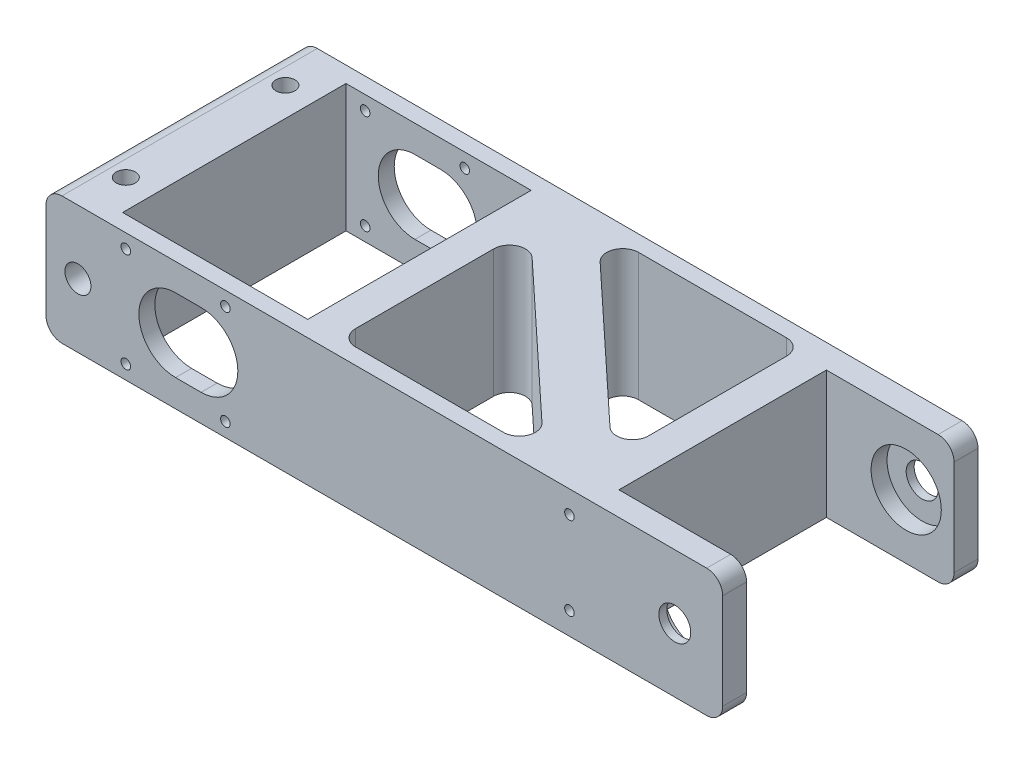
SolidWorks part; units mm, degrees
ref_plane "Front Plane" through (0, 0, 0) normal (0, 0, 1) x (1, 0, 0)
ref_plane "Top Plane" through (0, 0, 0) normal (0, 1, 0) x (1, 0, 0)
ref_plane "Right Plane" through (0, 0, 0) normal (1, 0, 0) x (0, 0, -1)
sketch "Sketch1" plane through (0, 0, 0) normal (0, 0, 1) x (1, 0, 0)
  line L0 (-106, -20) -> (-106, 20)
  line L1 (-106, 20) -> (106, 20)
  line L3 (-106, -20) -> (106, -20)
  line L4 (106, 20) -> (106, -20)
  line L5 (-106, 20) -> (106, -20) construction
  line L6 (-106, -20) -> (106, 20) construction
  line L7 (-81, 15.6) -> (-81, -15.6) construction
  line L8 (58, -13) -> (58, 13) construction
  line L9 (-81, 15.6) -> (-73, 15.6) construction
  line L10 (-81, 17.1) -> (-73, 17.1) construction
  line L11 (-81, 14.1) -> (-73, 14.1) construction
  line L12 (-49.8, 15.6) -> (-41.8, 15.6) construction
  line L13 (-49.8, 17.1) -> (-41.8, 17.1) construction
  line L14 (-49.8, 14.1) -> (-41.8, 14.1) construction
  line L15 (-81, -15.6) -> (-73, -15.6) construction
  line L16 (-81, -14.1) -> (-73, -14.1) construction
  line L17 (-81, -17.1) -> (-73, -17.1) construction
  line L18 (-49.8, -15.6) -> (-41.8, -15.6) construction
  line L19 (-49.8, -14.1) -> (-41.8, -14.1) construction
  line L20 (-49.8, -17.1) -> (-41.8, -17.1) construction
  line L21 (-65.4, 0) -> (-57.4, 0) construction
  line L22 (-65.4, 11.5) -> (-57.4, 11.5)
  line L23 (-65.4, -11.5) -> (-57.4, -11.5)
  circle A0 centre (-96, 0) radius 4.075
  circle A1 centre (-81, 15.6) radius 1.5
  circle A2 centre (-49.8, 15.6) radius 1.5
  circle A3 centre (-81, -15.6) radius 1.5
  circle A4 centre (-49.8, -15.6) radius 1.5
  circle A5 centre (-65.4, 0) radius 11.5 construction
  circle A6 centre (91, 0) radius 5
  arc A7 (-81, 17.1) -> (-81, 14.1) centre (-81, 15.6) ccw construction
  arc A8 (-73, 14.1) -> (-73, 17.1) centre (-73, 15.6) ccw construction
  arc A9 (-49.8, 17.1) -> (-49.8, 14.1) centre (-49.8, 15.6) ccw construction
  arc A10 (-41.8, 14.1) -> (-41.8, 17.1) centre (-41.8, 15.6) ccw construction
  arc A11 (-81, -14.1) -> (-81, -17.1) centre (-81, -15.6) ccw construction
  arc A12 (-73, -17.1) -> (-73, -14.1) centre (-73, -15.6) ccw construction
  arc A13 (-49.8, -14.1) -> (-49.8, -17.1) centre (-49.8, -15.6) ccw construction
  arc A14 (-41.8, -17.1) -> (-41.8, -14.1) centre (-41.8, -15.6) ccw construction
  arc A15 (-65.4, 11.5) -> (-65.4, -11.5) centre (-65.4, 0) ccw
  arc A16 (-57.4, -11.5) -> (-57.4, 11.5) centre (-57.4, 0) ccw
  circle A17 centre (58, 13) radius 1.5
  circle A18 centre (58, -13) radius 1.5
  point P0 (0, 0)
  point P16 (-81, 0)
  point P22 (-77, 15.6)
  point P28 (-45.8, 15.6)
  point P34 (-77, -15.6)
  point P40 (-45.8, -15.6)
  point P47 (-61.4, 0)
  point P50 (58, 0)
  dimension "D3" = 8.15
  dimension "D5" = 31.2
  dimension "D1" = 3
  dimension "D7" = 31.2
  dimension "D9" = 23
  dimension "D10" = 10
  dimension "D4" = 10
  dimension "D2" = 212
  dimension "D6" = 40
  dimension "D8" = 15
  dimension "D11" = 15
  dimension "D12" = 4
  dimension "D13" = 15.6
  dimension "D14" = 26
  dimension "D15" = 33
extrude "Boss-Extrude1" add sketch "Sketch1" along normal mid plane 80
sketch "Sketch2" plane through (0, 0, 0) normal (0, 1, 0) x (1, 0, 0)
  line L0 (-106, 40) -> (106, 40) construction
  line L1 (-87, 35) -> (-29, 35)
  line L2 (-87, 35) -> (-87, -35)
  line L3 (-87, -35) -> (-29, -35)
  line L4 (-29, 35) -> (-29, -35)
  line L5 (-87, 35) -> (-29, -35) construction
  line L6 (-87, -35) -> (-29, 35) construction
  line L7 (-19, 24.7409) -> (45.0081, -35)
  line L8 (106, -40) -> (106, 40) construction
  line L9 (66, 32.5) -> (106, 32.5)
  line L10 (66, 32.5) -> (66, -32.5)
  line L11 (66, -32.5) -> (106, -32.5)
  line L12 (106, 32.5) -> (106, -32.5)
  line L13 (66, 32.5) -> (106, -32.5) construction
  line L14 (66, -32.5) -> (106, 32.5) construction
  line L15 (-19, 35) -> (56, 35) construction
  line L16 (-19, 35) -> (-19, -35) construction
  line L17 (-19, -35) -> (56, -35) construction
  line L18 (56, 35) -> (56, -35) construction
  line L19 (-19, 35) -> (56, -35) construction
  line L20 (-19, -35) -> (56, 35) construction
  line L21 (-8.0081, 35) -> (56, -24.7409)
  line L22 (-19, 24.7409) -> (-19, -35)
  line L23 (-8.0081, 35) -> (56, 35)
  line L24 (56, 35) -> (56, -24.7409)
  line L25 (-19, -35) -> (45.0081, -35)
  line L26 (-106, -40) -> (106, -40) construction
  line L27 (-106, -40) -> (-106, 40) construction
  circle A0 centre (-96, 25) radius 1.5
  circle A1 centre (-96, -25) radius 1.5
  point P0 (-58, 0)
  point P10 (18.5, 0)
  point P11 (86, 0)
  point P30 (0, 0)
  dimension "D9" = 3
  dimension "D10" = 10
  dimension "D11" = 15
  dimension "D12" = 15
  dimension "D1" = 58
  dimension "D2" = 5
  dimension "D3" = 58
  dimension "D4" = 40
  dimension "D5" = 10
  dimension "D6" = 10
  dimension "D7" = 15
  dimension "D8" = 7.5
extrude "Cut-Extrude3" cut sketch "Sketch2" against normal through all both and the other way through all
fillet "Fillet1" radius 5 6 edges at (45.0081, 0, 35) (-19, 0, 35) (56, 0, 24.7409) (56, 0, -35) (-8.0081, 0, -35) (-19, 0, -24.7409)
fillet "Fillet2" radius 5 6 edges at (-106, 20, 0) (-106, -20, 0) (106, 20, 36.25) (106, -20, 36.25) (106, 20, -36.25) (106, -20, -36.25)
sketch "Sketch4" plane through (0, 0, 0) normal (0, 0, 1) x (1, 0, 0)
  circle A0 centre (91, 0) radius 11
  dimension "D1" = 22
extrude "Cut-Extrude4" cut sketch "Sketch4" against normal mid plane 75
sketch "Sketch5" plane through (0, 20, 0) normal (0, 1, 0) x (1, 0, 0)
  circle A0 centre (-96, 25) radius 3
  circle A1 centre (-96, -25) radius 3
  dimension "D1" = 6
extrude "Cut-Extrude5" cut sketch "Sketch5" against normal blind 5
